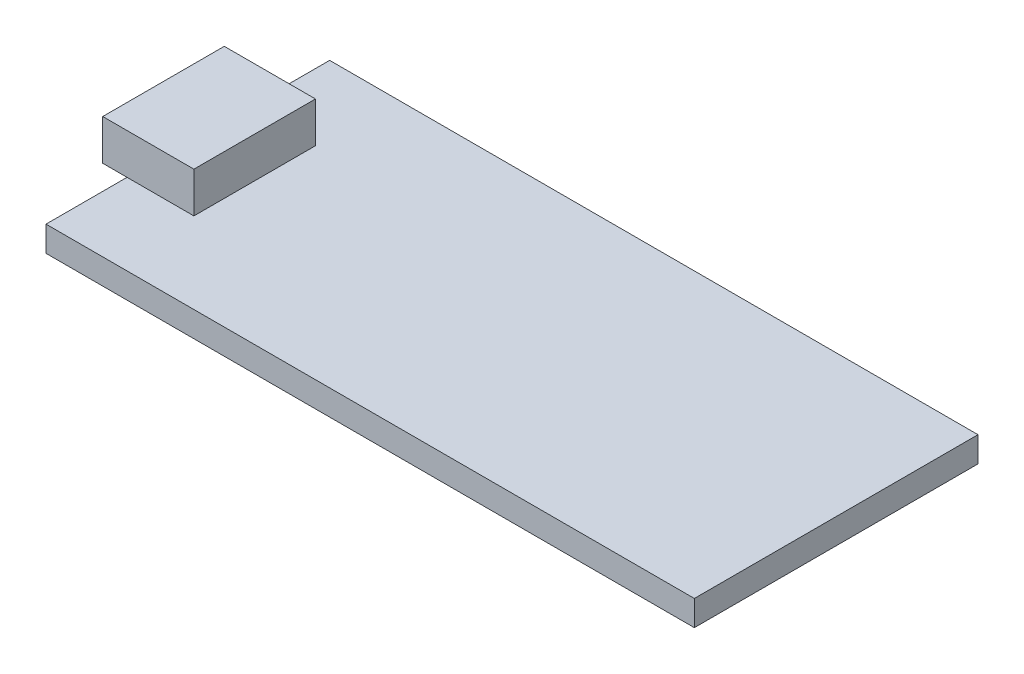
SolidWorks part; units mm, degrees
ref_plane "Front Plane" through (0, 0, 0) normal (0, 0, 1) x (1, 0, 0)
ref_plane "Top Plane" through (0, 0, 0) normal (0, 1, 0) x (1, 0, 0)
ref_plane "Right Plane" through (0, 0, 0) normal (1, 0, 0) x (0, 0, -1)
sketch "Sketch1" plane through (0, 0, 0) normal (0, 1, 0) x (1, 0, 0)
  line L1 (0, 0) -> (40.64, 0)
  line L2 (0, 0) -> (0, 17.78)
  line L3 (0, 17.78) -> (40.64, 17.78)
  line L4 (40.64, 0) -> (40.64, 17.78)
  dimension "D1" = 17.78
  dimension "D2" = 40.64
extrude "Boss-Extrude1" add sketch "Sketch1" along normal blind 1.5875
sketch "Sketch2" plane through (0, 1.5875, 0) normal (0, 1, 0) x (1, 0, 0)
  line L0 (0, 17.78) -> (0, 0) construction
  line L1 (-1.524, 12.7) -> (4.191, 12.7)
  line L2 (-1.524, 12.7) -> (-1.524, 5.08)
  line L3 (-1.524, 5.08) -> (4.191, 5.08)
  line L4 (4.191, 12.7) -> (4.191, 5.08)
  point P6 (-1.524, 8.89)
  point P7 (0, 8.89)
  dimension "D1" = 7.62
  dimension "D2" = 5.715
  dimension "D3" = 1.524
extrude "Boss-Extrude2" add sketch "Sketch2" along normal blind 2.54
